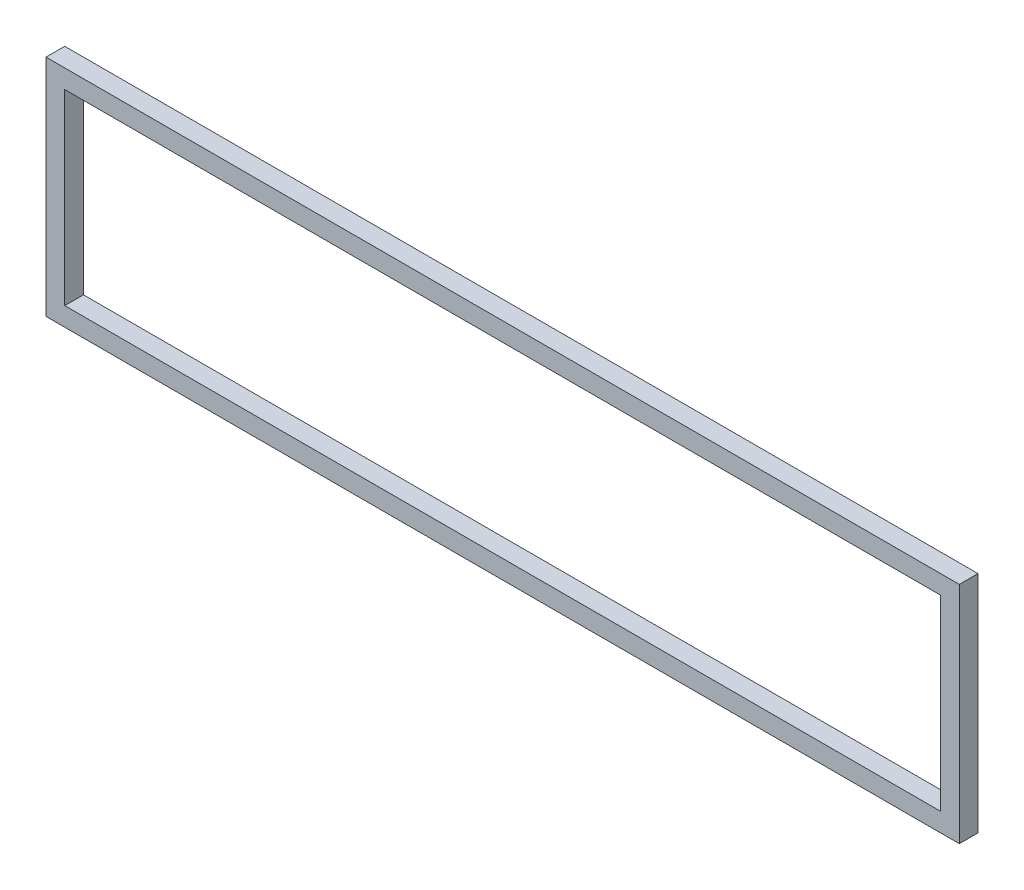
SolidWorks part; units mm, degrees
ref_plane "Front Plane" through (0, 0, 0) normal (0, 0, 1) x (1, 0, 0)
ref_plane "Top Plane" through (0, 0, 0) normal (0, 1, 0) x (1, 0, 0)
ref_plane "Right Plane" through (0, 0, 0) normal (1, 0, 0) x (0, 0, -1)
sketch "Sketch1" plane through (0, 0, 0) normal (0, 0, 1) x (1, 0, 0)
  line L0 (-643.617, -305.3191) -> (-643.617, 194.6809)
  line L1 (-693.617, -355.3191) -> (1746.383, -355.3191)
  line L2 (-693.617, -355.3191) -> (-693.617, 244.6809)
  line L3 (-693.617, 244.6809) -> (1746.383, 244.6809)
  line L4 (1746.383, -355.3191) -> (1746.383, 244.6809)
  line L5 (-643.617, 194.6809) -> (1696.383, 194.6809)
  line L6 (1696.383, -305.3191) -> (1696.383, 194.6809)
  line L7 (-643.617, -305.3191) -> (1696.383, -305.3191)
  dimension "D1" = 600
  dimension "D2" = 2440
  dimension "D3" = 50
extrude "Boss-Extrude1" add sketch "Sketch1" along normal blind 50
